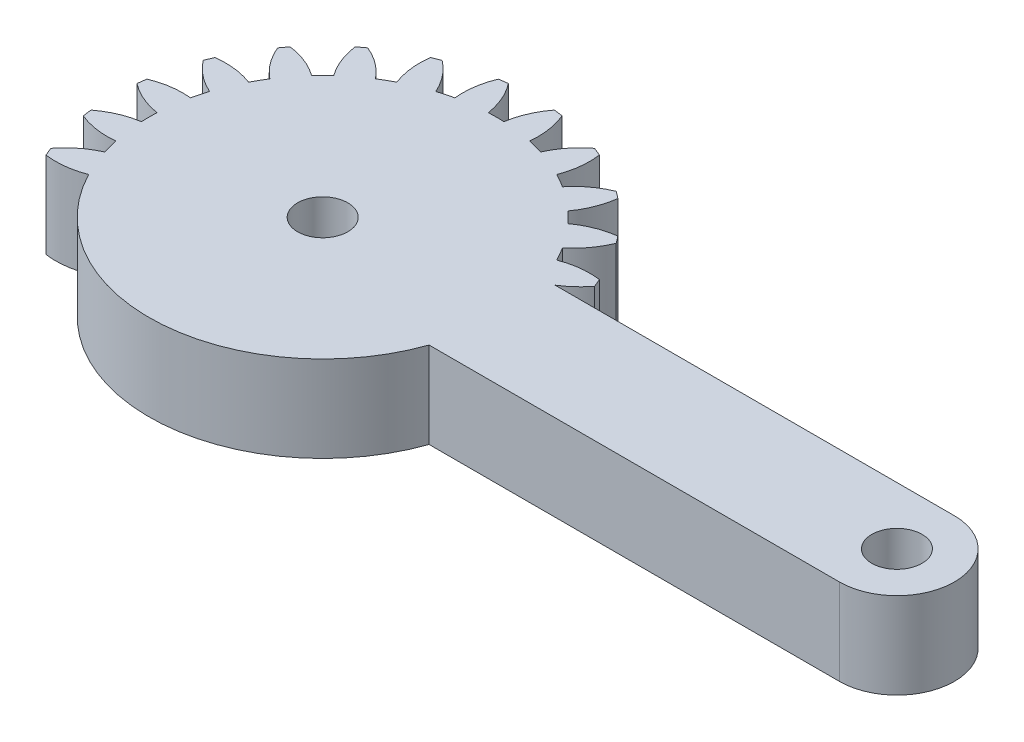
SolidWorks part; units mm, degrees
ref_plane "Front Plane" through (0, 0, 0) normal (0, 0, 1) x (1, 0, 0)
ref_plane "Top Plane" through (0, 0, 0) normal (0, 1, 0) x (1, 0, 0)
ref_plane "Right Plane" through (0, 0, 0) normal (1, 0, 0) x (0, 0, -1)
sketch "Sketch1" plane through (0, 0, 0) normal (0, 1, 0) x (1, 0, 0)
  line L0 (29.8937, 4) -> (2.0816, 4)
  line L1 (2.0816, -4) -> (29.8937, -4)
  arc A0 (2.0816, 4) -> (3.5217, 5.3071) centre (-0.7683, 8.5867) ccw
  arc A1 (3.5217, 5.3071) -> (3.2829, 5.8838) centre (-10.1063, 0) ccw
  arc A2 (3.2829, 5.8838) -> (0.6271, 5.5703) centre (2.5684, 0.5313) ccw
  arc A3 (0.6271, 5.5703) -> (0.0844, 6.5103) centre (-10.1063, 0) ccw
  arc A4 (0.0844, 6.5103) -> (1.6838, 8.6535) centre (-3.3089, 10.711) ccw
  arc A5 (1.6838, 8.6535) -> (1.3038, 9.1487) centre (-10.1063, 0) ccw
  arc A6 (1.3038, 9.1487) -> (-1.1803, 8.1585) centre (1.999, 3.7936) ccw
  arc A7 (-1.1803, 8.1585) -> (-1.9479, 8.926) centre (-10.1063, 0) ccw
  arc A8 (-1.9479, 8.926) -> (-0.9576, 11.4102) centre (-6.3127, 12.1053) ccw
  arc A9 (-0.9576, 11.4102) -> (-1.4528, 11.7901) centre (-10.1063, 0) ccw
  arc A10 (-1.4528, 11.7901) -> (-3.596, 10.1907) centre (0.6046, 6.7975) ccw
  arc A11 (-3.596, 10.1907) -> (-4.5361, 10.7334) centre (-10.1063, 0) ccw
  arc A12 (-4.5361, 10.7334) -> (-4.2225, 13.3892) centre (-9.5751, 12.6747) ccw
  arc A13 (-4.2225, 13.3892) -> (-4.7992, 13.6281) centre (-10.1063, 0) ccw
  arc A14 (-4.7992, 13.6281) -> (-6.4554, 11.5285) centre (-1.5196, 9.3381) ccw
  arc A15 (-6.4554, 11.5285) -> (-7.5039, 11.8094) centre (-10.1063, 0) ccw
  arc A16 (-7.5039, 11.8094) -> (-7.8884, 14.4558) centre (-12.8736, 12.3803) ccw
  arc A17 (-7.8884, 14.4558) -> (-8.5072, 14.5373) centre (-10.1063, 0) ccw
  arc A18 (-8.5072, 14.5373) -> (-9.5636, 12.0806) centre (-4.2291, 11.2423) ccw
  arc A19 (-9.5636, 12.0806) -> (-10.6491, 12.0806) centre (-10.1063, 0) ccw
  arc A20 (-10.6491, 12.0806) -> (-11.7054, 14.5373) centre (-15.9836, 11.2423) ccw
  arc A21 (-11.7054, 14.5373) -> (-12.3243, 14.4558) centre (-10.1063, 0) ccw
  arc A22 (-12.3243, 14.4558) -> (-12.7088, 11.8094) centre (-7.3391, 12.3803) ccw
  arc A23 (-12.7088, 11.8094) -> (-13.7573, 11.5285) centre (-10.1063, 0) ccw
  arc A24 (-13.7573, 11.5285) -> (-15.4135, 13.6281) centre (-18.6931, 9.3381) ccw
  arc A25 (-15.4135, 13.6281) -> (-15.9901, 13.3892) centre (-10.1063, 0) ccw
  arc A26 (-15.9901, 13.3892) -> (-15.6766, 10.7334) centre (-10.6376, 12.6747) ccw
  arc A27 (-15.6766, 10.7334) -> (-16.6166, 10.1907) centre (-10.1063, 0) ccw
  arc A28 (-16.6166, 10.1907) -> (-18.7599, 11.7901) centre (-20.8173, 6.7975) ccw
  arc A29 (-18.7599, 11.7901) -> (-19.255, 11.4102) centre (-10.1063, 0) ccw
  arc A30 (-19.255, 11.4102) -> (-18.2648, 8.926) centre (-13.9, 12.1053) ccw
  arc A31 (-18.2648, 8.926) -> (-19.0324, 8.1585) centre (-10.1063, 0) ccw
  arc A32 (-19.0324, 8.1585) -> (-21.5165, 9.1487) centre (-22.2117, 3.7936) ccw
  arc A33 (-21.5165, 9.1487) -> (-21.8965, 8.6535) centre (-10.1063, 0) ccw
  arc A34 (-21.8965, 8.6535) -> (-20.2971, 6.5103) centre (-16.9038, 10.711) ccw
  arc A35 (-20.2971, 6.5103) -> (-20.8398, 5.5703) centre (-10.1063, 0) ccw
  arc A36 (-20.8398, 5.5703) -> (-23.4956, 5.8838) centre (-22.7811, 0.5313) ccw
  arc A37 (-23.4956, 5.8838) -> (-23.7344, 5.3071) centre (-10.1063, 0) ccw
  arc A38 (-23.7344, 5.3071) -> (-21.6348, 3.6509) centre (-19.4444, 8.5867) ccw
  arc A39 (-21.6348, 3.6509) -> (-21.9157, 2.6025) centre (-10.1063, 0) ccw
  arc A40 (-21.9157, 2.6025) -> (-24.5622, 2.2179) centre (-22.4867, -2.7673) ccw
  arc A41 (-24.5622, 2.2179) -> (-24.6437, 1.5991) centre (-10.1063, 0) ccw
  arc A42 (-24.6437, 1.5991) -> (-22.1869, 0.5427) centre (-21.3486, 5.8773) ccw
  arc A43 (-22.1869, 0.5427) -> (-22.1869, -0.5427) centre (-10.1063, 0) ccw
  arc A44 (-22.1869, -0.5427) -> (-24.6437, -1.5991) centre (-21.3486, -5.8773) ccw
  arc A45 (-24.6437, -1.5991) -> (-24.5622, -2.2179) centre (-10.1063, 0) ccw
  arc A46 (-24.5622, -2.2179) -> (-21.9157, -2.6025) centre (-22.4867, 2.7673) ccw
  arc A47 (-21.9157, -2.6025) -> (-21.6348, -3.6509) centre (-10.1063, 0) ccw
  arc A48 (-21.6348, -3.6509) -> (-23.7344, -5.3071) centre (-19.4444, -8.5867) ccw
  arc A49 (-23.7344, -5.3071) -> (-23.4956, -5.8838) centre (-10.1063, 0) ccw
  arc A50 (-23.4956, -5.8838) -> (-20.8398, -5.5703) centre (-22.7811, -0.5313) ccw
  arc A51 (-20.8398, -5.5703) -> (-20.2971, -6.5103) centre (-10.1063, 0) ccw
  arc A52 (-20.2971, -6.5103) -> (-21.8965, -8.6535) centre (-16.9038, -10.711) ccw
  arc A53 (-21.8965, -8.6535) -> (-21.5165, -9.1487) centre (-10.1063, 0) ccw
  arc A54 (-21.5165, -9.1487) -> (-19.0324, -8.1585) centre (-22.2117, -3.7936) ccw
  arc A55 (-19.0324, -8.1585) -> (-18.2648, -8.926) centre (-10.1063, 0) ccw
  arc A56 (-18.2648, -8.926) -> (-19.255, -11.4102) centre (-13.9, -12.1053) ccw
  arc A57 (-19.255, -11.4102) -> (-18.7599, -11.7901) centre (-10.1063, 0) ccw
  arc A58 (-18.7599, -11.7901) -> (-16.6166, -10.1907) centre (-20.8173, -6.7975) ccw
  arc A59 (-16.6166, -10.1907) -> (-15.6766, -10.7334) centre (-10.1063, 0) ccw
  arc A60 (-15.6766, -10.7334) -> (-15.9901, -13.3892) centre (-10.6376, -12.6747) ccw
  arc A61 (-15.9901, -13.3892) -> (-15.4135, -13.6281) centre (-10.1063, 0) ccw
  arc A62 (-15.4135, -13.6281) -> (-13.7573, -11.5285) centre (-18.6931, -9.3381) ccw
  arc A63 (-13.7573, -11.5285) -> (-12.7088, -11.8094) centre (-10.1063, 0) ccw
  arc A64 (-12.7088, -11.8094) -> (-12.3243, -14.4558) centre (-7.3391, -12.3803) ccw
  arc A65 (-12.3243, -14.4558) -> (-11.7054, -14.5373) centre (-10.1063, 0) ccw
  arc A66 (-11.7054, -14.5373) -> (-10.6491, -12.0806) centre (-15.9836, -11.2423) ccw
  arc A67 (-10.6491, -12.0806) -> (-9.5636, -12.0806) centre (-10.1063, 0) ccw
  arc A68 (-9.5636, -12.0806) -> (-8.5072, -14.5373) centre (-4.2291, -11.2423) ccw
  arc A69 (-8.5072, -14.5373) -> (-7.8884, -14.4558) centre (-10.1063, 0) ccw
  arc A70 (-7.8884, -14.4558) -> (-7.5039, -11.8094) centre (-12.8736, -12.3803) ccw
  arc A71 (-7.5039, -11.8094) -> (-6.4554, -11.5285) centre (-10.1063, 0) ccw
  arc A72 (-6.4554, -11.5285) -> (-4.7992, -13.6281) centre (-1.5196, -9.3381) ccw
  arc A73 (-4.7992, -13.6281) -> (-4.2225, -13.3892) centre (-10.1063, 0) ccw
  arc A74 (-4.2225, -13.3892) -> (-4.5361, -10.7334) centre (-9.5751, -12.6747) ccw
  arc A75 (-4.5361, -10.7334) -> (-3.596, -10.1907) centre (-10.1063, 0) ccw
  arc A76 (-3.596, -10.1907) -> (-1.4528, -11.7901) centre (0.6046, -6.7975) ccw
  arc A77 (-1.4528, -11.7901) -> (-0.9576, -11.4102) centre (-10.1063, 0) ccw
  arc A78 (-0.9576, -11.4102) -> (-1.9479, -8.926) centre (-6.3127, -12.1053) ccw
  arc A79 (-1.9479, -8.926) -> (-1.1803, -8.1585) centre (-10.1063, 0) ccw
  arc A80 (-1.1803, -8.1585) -> (1.3038, -9.1487) centre (1.999, -3.7936) ccw
  arc A81 (1.3038, -9.1487) -> (1.6838, -8.6535) centre (-10.1063, 0) ccw
  arc A82 (1.6838, -8.6535) -> (0.0844, -6.5103) centre (-3.3089, -10.711) ccw
  arc A83 (0.0844, -6.5103) -> (0.6271, -5.5703) centre (-10.1063, 0) ccw
  arc A84 (0.6271, -5.5703) -> (3.2829, -5.8838) centre (2.5684, -0.5313) ccw
  arc A85 (3.2829, -5.8838) -> (3.5217, -5.3071) centre (-10.1063, 0) ccw
  arc A86 (3.5217, -5.3071) -> (2.0816, -4) centre (-0.7683, -8.5867) ccw
  arc A87 (29.8937, -4) -> (29.8937, 4) centre (29.8937, 0) ccw
  circle A88 centre (-10.1063, 0) radius 1.75
  circle A89 centre (29.8937, 0) radius 1.75
  dimension "D1" = 3.5
  dimension "D2" = 3.5
  dimension "D4" = 4
  dimension "D5" = 40
extrude "Boss-Extrude1" add sketch "Sketch1" along normal blind 4
sketch "Sketch2" plane through (0, 4, 0) normal (0, 1, 0) x (1, 0, 0)
  line L0 (2.0816, -4) -> (1.3057, -4)
  line L2 (29.8937, 4) -> (2.0816, 4)
  line L3 (2.0816, -4) -> (29.8937, -4)
  line L4 (29.8937, 4) -> (2.0816, 4)
  line L5 (2.0816, -4) -> (29.8937, -4)
  circle A0 centre (-10.1063, 0) radius 12.0927
  arc A88 (29.8937, -4) -> (29.8937, 4) centre (29.8937, 0) ccw
  arc A89 (2.0816, 4) -> (3.5217, 5.3071) centre (-0.7683, 8.5867) ccw
  arc A90 (3.5217, 5.3071) -> (3.2829, 5.8838) centre (-10.1063, 0) ccw
  arc A91 (3.2829, 5.8838) -> (0.6271, 5.5703) centre (2.5684, 0.5313) ccw
  arc A92 (0.6271, 5.5703) -> (0.0844, 6.5103) centre (-10.1063, 0) ccw
  arc A93 (0.0844, 6.5103) -> (1.6838, 8.6535) centre (-3.3089, 10.711) ccw
  arc A94 (1.6838, 8.6535) -> (1.3038, 9.1487) centre (-10.1063, 0) ccw
  arc A95 (1.3038, 9.1487) -> (-1.1803, 8.1585) centre (1.999, 3.7936) ccw
  arc A96 (-1.1803, 8.1585) -> (-1.9479, 8.926) centre (-10.1063, 0) ccw
  arc A97 (-1.9479, 8.926) -> (-0.9576, 11.4102) centre (-6.3127, 12.1053) ccw
  arc A98 (-0.9576, 11.4102) -> (-1.4528, 11.7901) centre (-10.1063, 0) ccw
  arc A99 (-1.4528, 11.7901) -> (-3.596, 10.1907) centre (0.6046, 6.7975) ccw
  arc A100 (-3.596, 10.1907) -> (-4.5361, 10.7334) centre (-10.1063, 0) ccw
  arc A101 (-4.5361, 10.7334) -> (-4.2225, 13.3892) centre (-9.5751, 12.6747) ccw
  arc A102 (-4.2225, 13.3892) -> (-4.7992, 13.6281) centre (-10.1063, 0) ccw
  arc A103 (-4.7992, 13.6281) -> (-6.4554, 11.5285) centre (-1.5196, 9.3381) ccw
  arc A104 (-6.4554, 11.5285) -> (-7.5039, 11.8094) centre (-10.1063, 0) ccw
  arc A105 (-7.5039, 11.8094) -> (-7.8884, 14.4558) centre (-12.8736, 12.3803) ccw
  arc A106 (-7.8884, 14.4558) -> (-8.5072, 14.5373) centre (-10.1063, 0) ccw
  arc A107 (-8.5072, 14.5373) -> (-9.5636, 12.0806) centre (-4.2291, 11.2423) ccw
  arc A108 (-9.5636, 12.0806) -> (-10.6491, 12.0806) centre (-10.1063, 0) ccw
  arc A109 (-10.6491, 12.0806) -> (-11.7054, 14.5373) centre (-15.9836, 11.2423) ccw
  arc A110 (-11.7054, 14.5373) -> (-12.3243, 14.4558) centre (-10.1063, 0) ccw
  arc A111 (-12.3243, 14.4558) -> (-12.7088, 11.8094) centre (-7.3391, 12.3803) ccw
  arc A112 (-12.7088, 11.8094) -> (-13.7573, 11.5285) centre (-10.1063, 0) ccw
  arc A113 (-13.7573, 11.5285) -> (-15.4135, 13.6281) centre (-18.6931, 9.3381) ccw
  arc A114 (-15.4135, 13.6281) -> (-15.9901, 13.3892) centre (-10.1063, 0) ccw
  arc A115 (-15.9901, 13.3892) -> (-15.6766, 10.7334) centre (-10.6376, 12.6747) ccw
  arc A116 (-15.6766, 10.7334) -> (-16.6166, 10.1907) centre (-10.1063, 0) ccw
  arc A117 (-16.6166, 10.1907) -> (-18.7599, 11.7901) centre (-20.8173, 6.7975) ccw
  arc A118 (-18.7599, 11.7901) -> (-19.255, 11.4102) centre (-10.1063, 0) ccw
  arc A119 (-19.255, 11.4102) -> (-18.2648, 8.926) centre (-13.9, 12.1053) ccw
  arc A120 (-18.2648, 8.926) -> (-19.0324, 8.1585) centre (-10.1063, 0) ccw
  arc A121 (-19.0324, 8.1585) -> (-21.5165, 9.1487) centre (-22.2117, 3.7936) ccw
  arc A122 (-21.5165, 9.1487) -> (-21.8965, 8.6535) centre (-10.1063, 0) ccw
  arc A123 (-21.8965, 8.6535) -> (-20.2971, 6.5103) centre (-16.9038, 10.711) ccw
  arc A124 (-20.2971, 6.5103) -> (-20.8398, 5.5703) centre (-10.1063, 0) ccw
  arc A125 (-20.8398, 5.5703) -> (-23.4956, 5.8838) centre (-22.7811, 0.5313) ccw
  arc A126 (-23.4956, 5.8838) -> (-23.7344, 5.3071) centre (-10.1063, 0) ccw
  arc A127 (-23.7344, 5.3071) -> (-21.6348, 3.6509) centre (-19.4444, 8.5867) ccw
  arc A128 (-21.6348, 3.6509) -> (-21.9157, 2.6025) centre (-10.1063, 0) ccw
  arc A129 (-21.9157, 2.6025) -> (-24.5622, 2.2179) centre (-22.4867, -2.7673) ccw
  arc A130 (-24.5622, 2.2179) -> (-24.6437, 1.5991) centre (-10.1063, 0) ccw
  arc A131 (-24.6437, 1.5991) -> (-22.1869, 0.5427) centre (-21.3486, 5.8773) ccw
  arc A132 (-22.1869, 0.5427) -> (-22.1869, -0.5427) centre (-10.1063, 0) ccw
  arc A133 (-22.1869, -0.5427) -> (-24.6437, -1.5991) centre (-21.3486, -5.8773) ccw
  arc A134 (-24.6437, -1.5991) -> (-24.5622, -2.2179) centre (-10.1063, 0) ccw
  arc A135 (-24.5622, -2.2179) -> (-21.9157, -2.6025) centre (-22.4867, 2.7673) ccw
  arc A136 (-21.9157, -2.6025) -> (-21.6348, -3.6509) centre (-10.1063, 0) ccw
  arc A137 (-21.6348, -3.6509) -> (-23.7344, -5.3071) centre (-19.4444, -8.5867) ccw
  arc A138 (-23.7344, -5.3071) -> (-23.4956, -5.8838) centre (-10.1063, 0) ccw
  arc A139 (-23.4956, -5.8838) -> (-20.8398, -5.5703) centre (-22.7811, -0.5313) ccw
  arc A140 (-20.8398, -5.5703) -> (-20.2971, -6.5103) centre (-10.1063, 0) ccw
  arc A141 (-20.2971, -6.5103) -> (-21.8965, -8.6535) centre (-16.9038, -10.711) ccw
  arc A142 (-21.8965, -8.6535) -> (-21.5165, -9.1487) centre (-10.1063, 0) ccw
  arc A143 (-21.5165, -9.1487) -> (-19.0324, -8.1585) centre (-22.2117, -3.7936) ccw
  arc A144 (-19.0324, -8.1585) -> (-18.2648, -8.926) centre (-10.1063, 0) ccw
  arc A145 (-18.2648, -8.926) -> (-19.255, -11.4102) centre (-13.9, -12.1053) ccw
  arc A146 (-19.255, -11.4102) -> (-18.7599, -11.7901) centre (-10.1063, 0) ccw
  arc A147 (-18.7599, -11.7901) -> (-16.6166, -10.1907) centre (-20.8173, -6.7975) ccw
  arc A148 (-16.6166, -10.1907) -> (-15.6766, -10.7334) centre (-10.1063, 0) ccw
  arc A149 (-15.6766, -10.7334) -> (-15.9901, -13.3892) centre (-10.6376, -12.6747) ccw
  arc A150 (-15.9901, -13.3892) -> (-15.4135, -13.6281) centre (-10.1063, 0) ccw
  arc A151 (-15.4135, -13.6281) -> (-13.7573, -11.5285) centre (-18.6931, -9.3381) ccw
  arc A152 (-13.7573, -11.5285) -> (-12.7088, -11.8094) centre (-10.1063, 0) ccw
  arc A153 (-12.7088, -11.8094) -> (-12.3243, -14.4558) centre (-7.3391, -12.3803) ccw
  arc A154 (-12.3243, -14.4558) -> (-11.7054, -14.5373) centre (-10.1063, 0) ccw
  arc A155 (-11.7054, -14.5373) -> (-10.6491, -12.0806) centre (-15.9836, -11.2423) ccw
  arc A156 (-10.6491, -12.0806) -> (-9.5636, -12.0806) centre (-10.1063, 0) ccw
  arc A157 (-9.5636, -12.0806) -> (-8.5072, -14.5373) centre (-4.2291, -11.2423) ccw
  arc A158 (-8.5072, -14.5373) -> (-7.8884, -14.4558) centre (-10.1063, 0) ccw
  arc A159 (-7.8884, -14.4558) -> (-7.5039, -11.8094) centre (-12.8736, -12.3803) ccw
  arc A160 (-7.5039, -11.8094) -> (-6.4554, -11.5285) centre (-10.1063, 0) ccw
  arc A161 (-6.4554, -11.5285) -> (-4.7992, -13.6281) centre (-1.5196, -9.3381) ccw
  arc A162 (-4.7992, -13.6281) -> (-4.2225, -13.3892) centre (-10.1063, 0) ccw
  arc A163 (-4.2225, -13.3892) -> (-4.5361, -10.7334) centre (-9.5751, -12.6747) ccw
  arc A164 (-4.5361, -10.7334) -> (-3.596, -10.1907) centre (-10.1063, 0) ccw
  arc A165 (-3.596, -10.1907) -> (-1.4528, -11.7901) centre (0.6046, -6.7975) ccw
  arc A166 (-1.4528, -11.7901) -> (-0.9576, -11.4102) centre (-10.1063, 0) ccw
  arc A167 (-0.9576, -11.4102) -> (-1.9479, -8.926) centre (-6.3127, -12.1053) ccw
  arc A168 (-1.9479, -8.926) -> (-1.1803, -8.1585) centre (-10.1063, 0) ccw
  arc A169 (-1.1803, -8.1585) -> (1.3038, -9.1487) centre (1.999, -3.7936) ccw
  arc A170 (1.3038, -9.1487) -> (1.6838, -8.6535) centre (-10.1063, 0) ccw
  arc A171 (1.6838, -8.6535) -> (0.0844, -6.5103) centre (-3.3089, -10.711) ccw
  arc A172 (0.0844, -6.5103) -> (0.6271, -5.5703) centre (-10.1063, 0) ccw
  arc A173 (0.6271, -5.5703) -> (3.2829, -5.8838) centre (2.5684, -0.5313) ccw
  arc A174 (3.2829, -5.8838) -> (3.5217, -5.3071) centre (-10.1063, 0) ccw
  arc A175 (3.5217, -5.3071) -> (2.0816, -4) centre (-0.7683, -8.5867) ccw
  arc A176 (29.8937, -4) -> (29.8937, 4) centre (29.8937, 0) ccw
  arc A177 (2.0816, 4) -> (3.5217, 5.3071) centre (-0.7683, 8.5867) ccw
  arc A178 (3.5217, 5.3071) -> (3.2829, 5.8838) centre (-10.1063, 0) ccw
  arc A179 (3.2829, 5.8838) -> (0.6271, 5.5703) centre (2.5684, 0.5313) ccw
  arc A180 (0.6271, 5.5703) -> (0.0844, 6.5103) centre (-10.1063, 0) ccw
  arc A181 (0.0844, 6.5103) -> (1.6838, 8.6535) centre (-3.3089, 10.711) ccw
  arc A182 (1.6838, 8.6535) -> (1.3038, 9.1487) centre (-10.1063, 0) ccw
  arc A183 (1.3038, 9.1487) -> (-1.1803, 8.1585) centre (1.999, 3.7936) ccw
  arc A184 (-1.1803, 8.1585) -> (-1.9479, 8.926) centre (-10.1063, 0) ccw
  arc A185 (-1.9479, 8.926) -> (-0.9576, 11.4102) centre (-6.3127, 12.1053) ccw
  arc A186 (-0.9576, 11.4102) -> (-1.4528, 11.7901) centre (-10.1063, 0) ccw
  arc A187 (-1.4528, 11.7901) -> (-3.596, 10.1907) centre (0.6046, 6.7975) ccw
  arc A188 (-3.596, 10.1907) -> (-4.5361, 10.7334) centre (-10.1063, 0) ccw
  arc A189 (-4.5361, 10.7334) -> (-4.2225, 13.3892) centre (-9.5751, 12.6747) ccw
  arc A190 (-4.2225, 13.3892) -> (-4.7992, 13.6281) centre (-10.1063, 0) ccw
  arc A191 (-4.7992, 13.6281) -> (-6.4554, 11.5285) centre (-1.5196, 9.3381) ccw
  arc A192 (-6.4554, 11.5285) -> (-7.5039, 11.8094) centre (-10.1063, 0) ccw
  arc A193 (-7.5039, 11.8094) -> (-7.8884, 14.4558) centre (-12.8736, 12.3803) ccw
  arc A194 (-7.8884, 14.4558) -> (-8.5072, 14.5373) centre (-10.1063, 0) ccw
  arc A195 (-8.5072, 14.5373) -> (-9.5636, 12.0806) centre (-4.2291, 11.2423) ccw
  arc A196 (-9.5636, 12.0806) -> (-10.6491, 12.0806) centre (-10.1063, 0) ccw
  arc A197 (-10.6491, 12.0806) -> (-11.7054, 14.5373) centre (-15.9836, 11.2423) ccw
  arc A198 (-11.7054, 14.5373) -> (-12.3243, 14.4558) centre (-10.1063, 0) ccw
  arc A199 (-12.3243, 14.4558) -> (-12.7088, 11.8094) centre (-7.3391, 12.3803) ccw
  arc A200 (-12.7088, 11.8094) -> (-13.7573, 11.5285) centre (-10.1063, 0) ccw
  arc A201 (-13.7573, 11.5285) -> (-15.4135, 13.6281) centre (-18.6931, 9.3381) ccw
  arc A202 (-15.4135, 13.6281) -> (-15.9901, 13.3892) centre (-10.1063, 0) ccw
  arc A203 (-15.9901, 13.3892) -> (-15.6766, 10.7334) centre (-10.6376, 12.6747) ccw
  arc A204 (-15.6766, 10.7334) -> (-16.6166, 10.1907) centre (-10.1063, 0) ccw
  arc A205 (-16.6166, 10.1907) -> (-18.7599, 11.7901) centre (-20.8173, 6.7975) ccw
  arc A206 (-18.7599, 11.7901) -> (-19.255, 11.4102) centre (-10.1063, 0) ccw
  arc A207 (-19.255, 11.4102) -> (-18.2648, 8.926) centre (-13.9, 12.1053) ccw
  arc A208 (-18.2648, 8.926) -> (-19.0324, 8.1585) centre (-10.1063, 0) ccw
  arc A209 (-19.0324, 8.1585) -> (-21.5165, 9.1487) centre (-22.2117, 3.7936) ccw
  arc A210 (-21.5165, 9.1487) -> (-21.8965, 8.6535) centre (-10.1063, 0) ccw
  arc A211 (-21.8965, 8.6535) -> (-20.2971, 6.5103) centre (-16.9038, 10.711) ccw
  arc A212 (-20.2971, 6.5103) -> (-20.8398, 5.5703) centre (-10.1063, 0) ccw
  arc A213 (-20.8398, 5.5703) -> (-23.4956, 5.8838) centre (-22.7811, 0.5313) ccw
  arc A214 (-23.4956, 5.8838) -> (-23.7344, 5.3071) centre (-10.1063, 0) ccw
  arc A215 (-23.7344, 5.3071) -> (-21.6348, 3.6509) centre (-19.4444, 8.5867) ccw
  arc A216 (-21.6348, 3.6509) -> (-21.9157, 2.6025) centre (-10.1063, 0) ccw
  arc A217 (-21.9157, 2.6025) -> (-24.5622, 2.2179) centre (-22.4867, -2.7673) ccw
  arc A218 (-24.5622, 2.2179) -> (-24.6437, 1.5991) centre (-10.1063, 0) ccw
  arc A219 (-24.6437, 1.5991) -> (-22.1869, 0.5427) centre (-21.3486, 5.8773) ccw
  arc A220 (-22.1869, 0.5427) -> (-22.1869, -0.5427) centre (-10.1063, 0) ccw
  arc A221 (-22.1869, -0.5427) -> (-24.6437, -1.5991) centre (-21.3486, -5.8773) ccw
  arc A222 (-24.6437, -1.5991) -> (-24.5622, -2.2179) centre (-10.1063, 0) ccw
  arc A223 (-24.5622, -2.2179) -> (-21.9157, -2.6025) centre (-22.4867, 2.7673) ccw
  arc A224 (-21.9157, -2.6025) -> (-21.6348, -3.6509) centre (-10.1063, 0) ccw
  arc A225 (-21.6348, -3.6509) -> (-23.7344, -5.3071) centre (-19.4444, -8.5867) ccw
  arc A226 (-23.7344, -5.3071) -> (-23.4956, -5.8838) centre (-10.1063, 0) ccw
  arc A227 (-23.4956, -5.8838) -> (-20.8398, -5.5703) centre (-22.7811, -0.5313) ccw
  arc A228 (-20.8398, -5.5703) -> (-20.2971, -6.5103) centre (-10.1063, 0) ccw
  arc A229 (-20.2971, -6.5103) -> (-21.8965, -8.6535) centre (-16.9038, -10.711) ccw
  arc A230 (-21.8965, -8.6535) -> (-21.5165, -9.1487) centre (-10.1063, 0) ccw
  arc A231 (-21.5165, -9.1487) -> (-19.0324, -8.1585) centre (-22.2117, -3.7936) ccw
  arc A232 (-19.0324, -8.1585) -> (-18.2648, -8.926) centre (-10.1063, 0) ccw
  arc A233 (-18.2648, -8.926) -> (-19.255, -11.4102) centre (-13.9, -12.1053) ccw
  arc A234 (-19.255, -11.4102) -> (-18.7599, -11.7901) centre (-10.1063, 0) ccw
  arc A235 (-18.7599, -11.7901) -> (-16.6166, -10.1907) centre (-20.8173, -6.7975) ccw
  arc A236 (-16.6166, -10.1907) -> (-15.6766, -10.7334) centre (-10.1063, 0) ccw
  arc A237 (-15.6766, -10.7334) -> (-15.9901, -13.3892) centre (-10.6376, -12.6747) ccw
  arc A238 (-15.9901, -13.3892) -> (-15.4135, -13.6281) centre (-10.1063, 0) ccw
  arc A239 (-15.4135, -13.6281) -> (-13.7573, -11.5285) centre (-18.6931, -9.3381) ccw
  arc A240 (-13.7573, -11.5285) -> (-12.7088, -11.8094) centre (-10.1063, 0) ccw
  arc A241 (-12.7088, -11.8094) -> (-12.3243, -14.4558) centre (-7.3391, -12.3803) ccw
  arc A242 (-12.3243, -14.4558) -> (-11.7054, -14.5373) centre (-10.1063, 0) ccw
  arc A243 (-11.7054, -14.5373) -> (-10.6491, -12.0806) centre (-15.9836, -11.2423) ccw
  arc A244 (-10.6491, -12.0806) -> (-9.5636, -12.0806) centre (-10.1063, 0) ccw
  arc A245 (-9.5636, -12.0806) -> (-8.5072, -14.5373) centre (-4.2291, -11.2423) ccw
  arc A246 (-8.5072, -14.5373) -> (-7.8884, -14.4558) centre (-10.1063, 0) ccw
  arc A247 (-7.8884, -14.4558) -> (-7.5039, -11.8094) centre (-12.8736, -12.3803) ccw
  arc A248 (-7.5039, -11.8094) -> (-6.4554, -11.5285) centre (-10.1063, 0) ccw
  arc A249 (-6.4554, -11.5285) -> (-4.7992, -13.6281) centre (-1.5196, -9.3381) ccw
  arc A250 (-4.7992, -13.6281) -> (-4.2225, -13.3892) centre (-10.1063, 0) ccw
  arc A251 (-4.2225, -13.3892) -> (-4.5361, -10.7334) centre (-9.5751, -12.6747) ccw
  arc A252 (-4.5361, -10.7334) -> (-3.596, -10.1907) centre (-10.1063, 0) ccw
  arc A253 (-3.596, -10.1907) -> (-1.4528, -11.7901) centre (0.6046, -6.7975) ccw
  arc A254 (-1.4528, -11.7901) -> (-0.9576, -11.4102) centre (-10.1063, 0) ccw
  arc A255 (-0.9576, -11.4102) -> (-1.9479, -8.926) centre (-6.3127, -12.1053) ccw
  arc A256 (-1.9479, -8.926) -> (-1.1803, -8.1585) centre (-10.1063, 0) ccw
  arc A257 (-1.1803, -8.1585) -> (1.3038, -9.1487) centre (1.999, -3.7936) ccw
  arc A258 (1.3038, -9.1487) -> (1.6838, -8.6535) centre (-10.1063, 0) ccw
  arc A259 (1.6838, -8.6535) -> (0.0844, -6.5103) centre (-3.3089, -10.711) ccw
  arc A260 (0.0844, -6.5103) -> (0.6271, -5.5703) centre (-10.1063, 0) ccw
  arc A261 (0.6271, -5.5703) -> (3.2829, -5.8838) centre (2.5684, -0.5313) ccw
  arc A262 (3.2829, -5.8838) -> (3.5217, -5.3071) centre (-10.1063, 0) ccw
  arc A263 (3.5217, -5.3071) -> (2.0816, -4) centre (-0.7683, -8.5867) ccw
  dimension "D1" = 0
extrude "Cut-Extrude1" cut sketch "Sketch2" against normal blind 10 contours A230 A231 A0 A229 | A234 A235 A0 A233 | A238 A239 A0 A237 | A242 A243 A0 A241 | A246 A247 A0 A245 | A250 A251 A0 A249 | A254 A255 A0 A253 | A258 A259 A0 A257 | A262 A263 L0 A0 A261
other "Move Face1" face at (29.8937, 0, 1.75) parameters "D1"=2
sketch "Sketch3" plane through (0, 4, 0) normal (0, 1, 0) x (1, 0, 0)
  circle A0 centre (-10.1063, 0) radius 13.45 construction
  circle A1 centre (-10.1063, 0) radius 13.45
